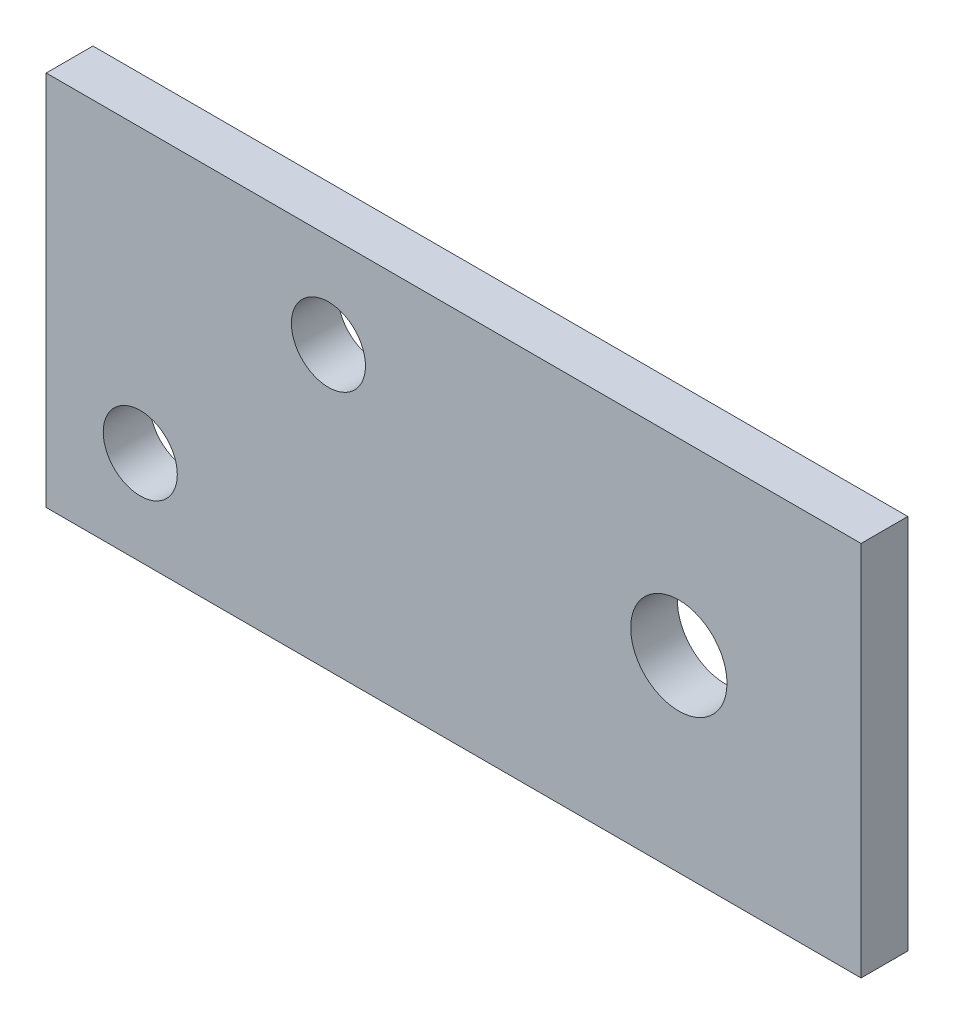
SolidWorks part; units mm, degrees
ref_plane "Alzado" through (0, 0, 0) normal (0, 0, 1) x (1, 0, 0)
ref_plane "Planta" through (0, 0, 0) normal (0, 1, 0) x (1, 0, 0)
ref_plane "Vista lateral" through (0, 0, 0) normal (1, 0, 0) x (0, 0, -1)
sketch "Croquis1" plane through (0, 0, 0) normal (0, 0, 1) x (1, 0, 0)
  line L0 (-59.2, 50.8) -> (-110, 50.8)
  line L1 (-110, 50.8) -> (-110, 0)
  line L2 (-110, 0) -> (0, 0)
  line L3 (0, 0) -> (0, 50.8)
  line L4 (0, 50.8) -> (-59.2, 50.8)
  circle A0 centre (-24.6, 25.4013) radius 6.5013
  dimension "D3" = 13.0027
  dimension "D1" = 110
  dimension "D2" = 50.8
  dimension "D4" = 25.4013
  dimension "D5" = 24.6
  dimension "D6" = 50.8
extrude "Saliente-Extruir1" add sketch "Croquis1" along normal blind 6.31
sketch "Croquis2" plane through (0, 0, 0) normal (0, 0, -1) x (-1, 0, 0)
  circle A0 centre (97.3, 12.7) radius 5
  circle A1 centre (71.9, 38.1) radius 5
extrude "Cortar-Extruir1" cut sketch "Croquis2" against normal blind 10
